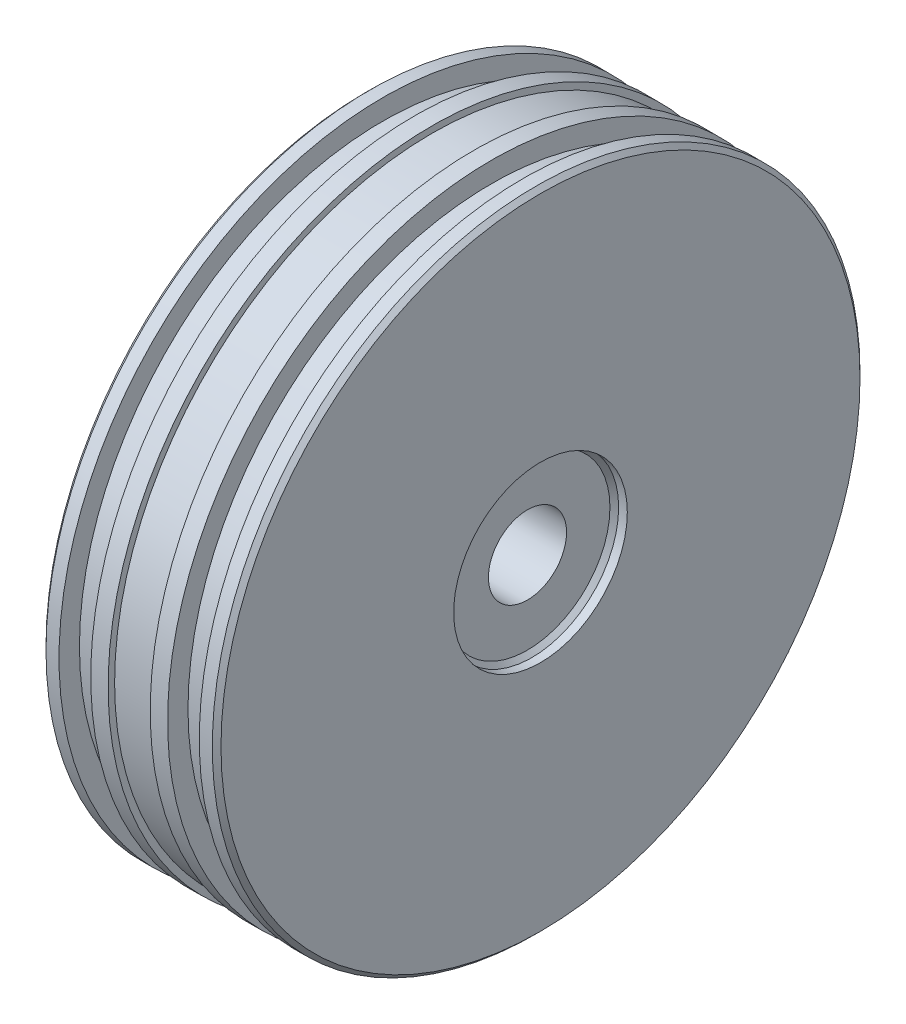
SolidWorks part; units mm, degrees
material "UHMW PRETO"
ref_plane "Спереди" through (0, 0, 0) normal (0, 0, 1) x (1, 0, 0)
ref_plane "Сверху" through (0, 0, 0) normal (0, 1, 0) x (1, 0, 0)
ref_plane "Справа" through (0, 0, 0) normal (1, 0, 0) x (0, 0, -1)
sketch "Эскиз1" plane through (0, 0, 0) normal (0, 0, 1) x (1, 0, 0)
  line L0 (0, 0) -> (-71.8572, 0) construction
  line L1 (0, 20) -> (0, 74.59)
  line L2 (0, 74.59) -> (4, 74.59)
  line L3 (40.3, 74.59) -> (40.3, 20)
  line L4 (0, 20) -> (15, 20)
  line L5 (11.3, 74.59) -> (15.3, 74.59)
  line L6 (25, 74.59) -> (29, 74.59)
  line L7 (36.3, 74.59) -> (40.3, 74.59)
  line L8 (15, 9) -> (37.3, 9)
  line L9 (37.3, 9) -> (37.3, 20)
  line L10 (37.3, 20) -> (40.3, 20)
  line L11 (15, 20) -> (15, 9)
  line L12 (0, 49.3173) -> (40.3, 49.3173) construction
  line L13 (4, 74.59) -> (4, 69.89)
  line L14 (4, 69.89) -> (11.3, 69.89)
  line L15 (11.3, 69.89) -> (11.3, 74.59)
  line L16 (15.3, 74.59) -> (15.3, 73.09)
  line L17 (15.3, 73.09) -> (25, 73.09)
  line L18 (25, 73.09) -> (25, 74.59)
  line L19 (29, 74.59) -> (29, 69.89)
  line L20 (29, 69.89) -> (36.3, 69.89)
  line L21 (36.3, 69.89) -> (36.3, 74.59)
  line L22 (20.15, 49.3173) -> (20.15, 9) construction
  dimension "D3" = 7.3
  dimension "D1" = 149.18
  dimension "D2" = 4
  dimension "D5" = 4.7
  dimension "D6" = 18
  dimension "D7" = 1.5
  dimension "D8" = 15
  dimension "D9" = 40
  dimension "D10" = 3
  dimension "D11" = 9.7
  dimension "D12" = 4
revolve "Повернуть1" add sketch "Эскиз1" angle 360 about L0
chamfer "Фаска1" distance 1 angle 45 2 edges at (40.3, 0, -74.59) (0, 0, -74.59)
chamfer "Фаска2" distance 3 angle 45 1 edges at (15, 0, -20)
chamfer "Фаска3" distance 1 angle 45 2 edges at (37.3, 0, -20) (0, 0, -20)
